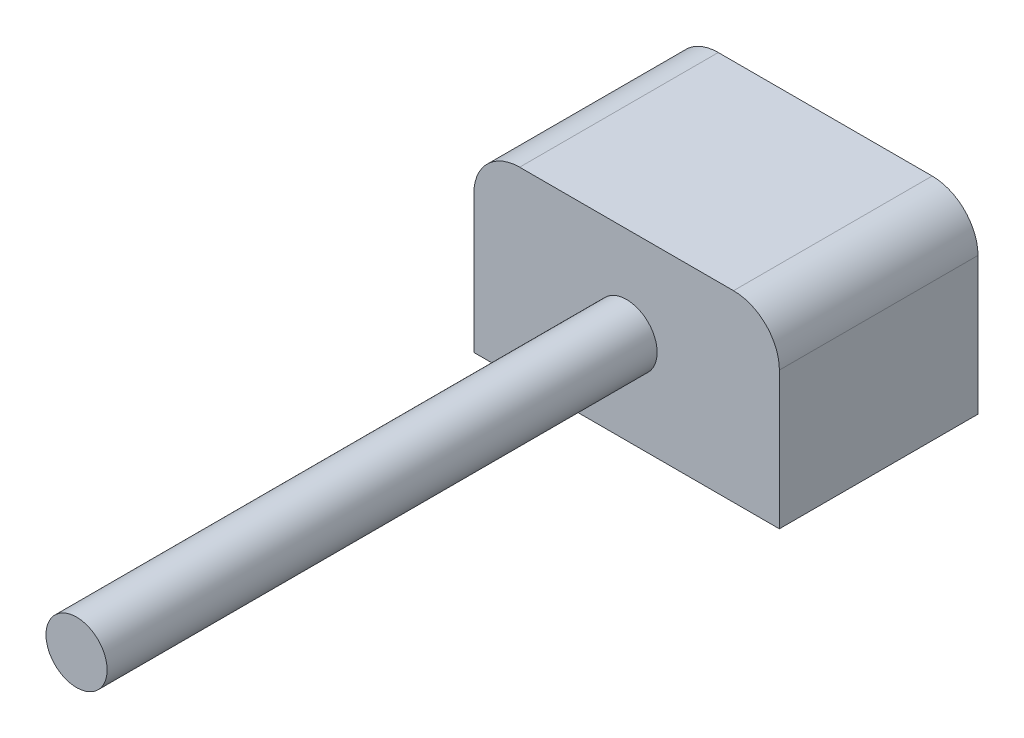
SolidWorks part; units mm, degrees
ref_plane "Ebene vorne" through (0, 0, 0) normal (0, 0, 1) x (1, 0, 0)
ref_plane "Ebene oben" through (0, 0, 0) normal (0, 1, 0) x (1, 0, 0)
ref_plane "Ebene rechts" through (0, 0, 0) normal (1, 0, 0) x (0, 0, -1)
sketch "Skizze1" plane through (0, 0, 0) normal (0, 0, 1) x (1, 0, 0)
  line L1 (100, 60) -> (-100, 60)
  line L2 (100, 60) -> (100, -60)
  line L3 (100, -60) -> (-100, -60)
  line L4 (-100, 60) -> (-100, -60)
  line L5 (100, 60) -> (-100, -60) construction
  line L6 (100, -60) -> (-100, 60) construction
  point P0 (0, 0)
  dimension "D1" = 200
  dimension "D2" = 120
extrude "Aufsatz-Linear austragen1" add sketch "Skizze1" along normal blind 130
sketch "Skizze2" plane through (0, 0, 130) normal (0, 0, 1) x (1, 0, 0)
  circle A0 centre (0, 0) radius 20
extrude "Aufsatz-Linear austragen2" add sketch "Skizze2" along normal blind 360
fillet "Verrundung1" radius 30 2 edges at (100, 60, 65) (-100, 60, 65)
